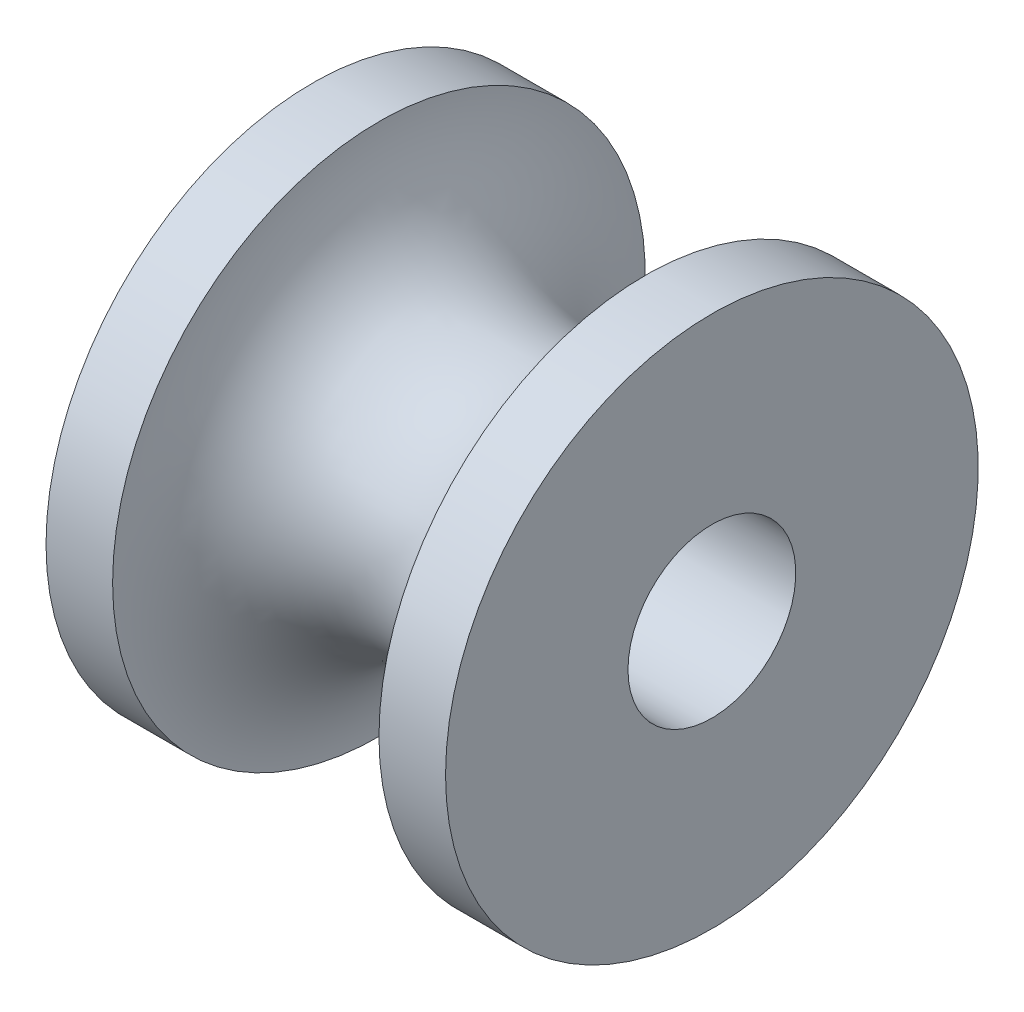
SolidWorks part; units mm, degrees
material "Custom Plastic"
ref_plane "Front" through (0, 0, 0) normal (0, 0, 1) x (1, 0, 0)
ref_plane "Top" through (0, 0, 0) normal (0, 1, 0) x (1, 0, 0)
ref_plane "Right" through (0, 0, 0) normal (1, 0, 0) x (0, 0, -1)
sketch "Sketch1" plane through (0, 0, 0) normal (1, 0, 0) x (0, 0, -1)
  circle A0 centre (0, 0) radius 1
  circle A1 centre (0, 0) radius 3.175
  dimension "D1" = 2
  dimension "D2" = 6.35
extrude "Boss-Extrude1" add sketch "Sketch1" along normal mid plane 4.7625
sketch "Sketch2" plane through (0, 0, 0) normal (0, 1, 0) x (1, 0, 0)
  line L0 (-2.3813, -3.175) -> (2.3813, -3.175) construction
  circle A0 centre (0, -3.175) radius 1.5875
  point P3 (0, 0)
  dimension "D1" = 3.175
revolve "Cut-Revolve1" cut sketch "Sketch2" angle 360 about axis through (2.3813, 0, 0) along (-1, 0, 0)
